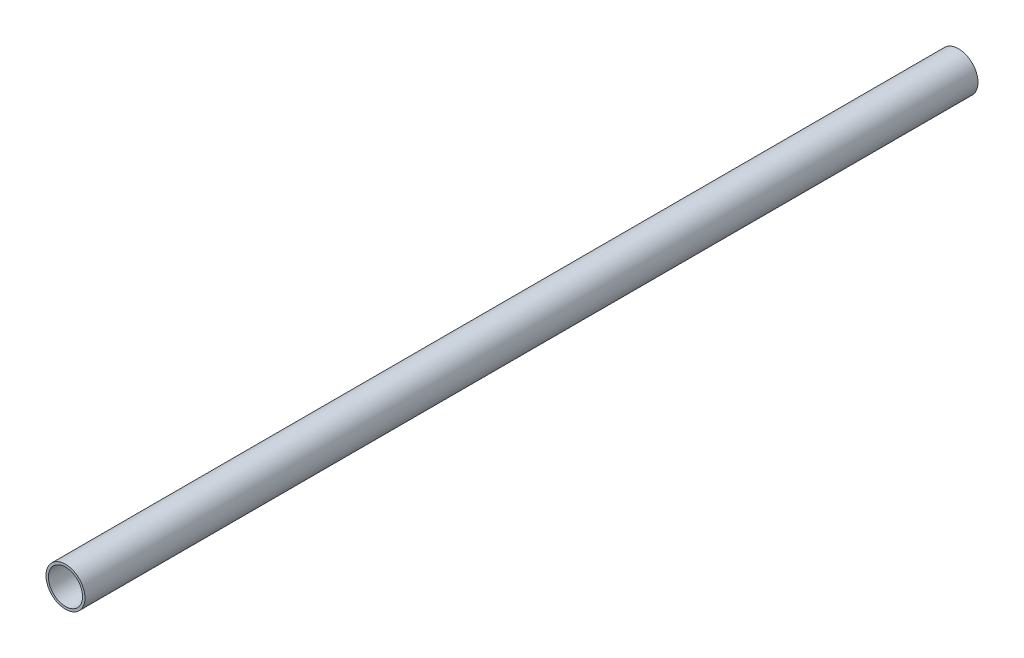
SolidWorks part; units mm, degrees
material "PC High Viscosity"
ref_plane "Front Plane" through (0, 0, 0) normal (0, 0, 1) x (1, 0, 0)
ref_plane "Top Plane" through (0, 0, 0) normal (0, 1, 0) x (1, 0, 0)
ref_plane "Right Plane" through (0, 0, 0) normal (1, 0, 0) x (0, 0, -1)
sketch "Sketch2" plane through (0, 0, 0) normal (0, 0, 1) x (1, 0, 0)
  circle A0 centre (0, 0) radius 11.1125
  circle A1 centre (0, 0) radius 12.7
  dimension "D1" = 25.4
  dimension "D2" = 22.225
extrude "Boss-Extrude1" add sketch "Sketch2" along normal mid plane 581.044
